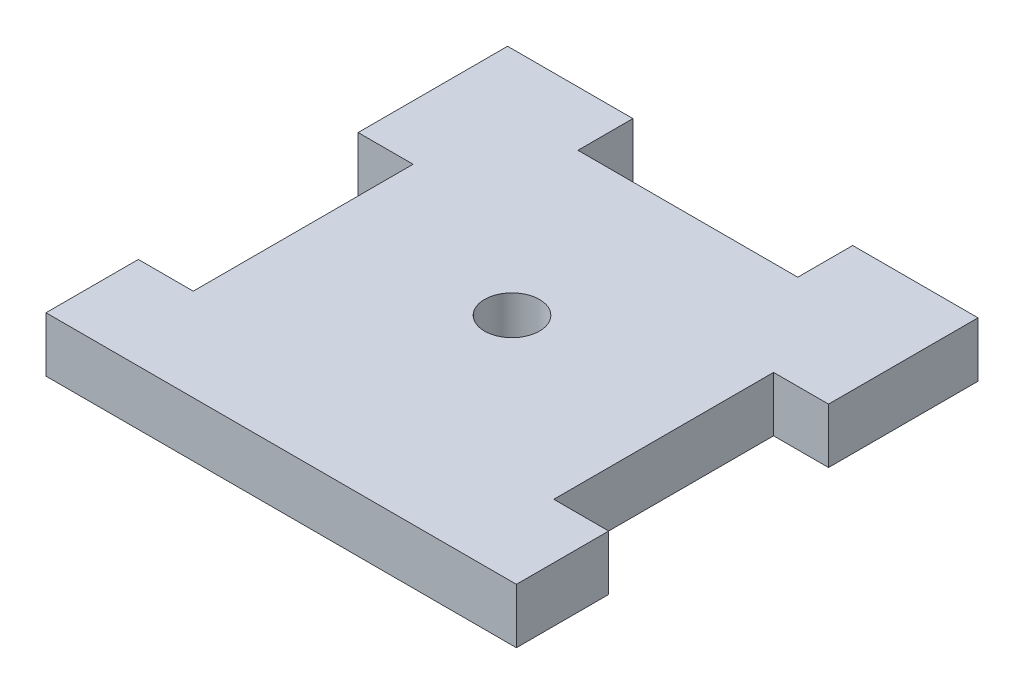
SolidWorks part; units mm, degrees
ref_plane "Front Plane" through (0, 0, 0) normal (0, 0, 1) x (1, 0, 0)
ref_plane "Top Plane" through (0, 0, 0) normal (0, 1, 0) x (1, 0, 0)
ref_plane "Right Plane" through (0, 0, 0) normal (1, 0, 0) x (0, 0, -1)
sketch "Sketch1" plane through (0, 0, 0) normal (0, 1, 0) x (1, 0, 0)
  line L0 (14.478, 53.34) -> (14.478, 46.99)
  line L1 (0, 0) -> (54.356, 0)
  line L2 (0, 0) -> (0, 10.668)
  line L3 (0, 53.34) -> (14.478, 53.34)
  line L4 (54.356, 0) -> (54.356, 10.668)
  line L5 (14.478, 46.99) -> (39.878, 46.99)
  line L6 (39.878, 46.99) -> (39.878, 53.34)
  line L7 (0, 36.068) -> (0, 53.34)
  line L8 (0, 36.068) -> (6.35, 36.068)
  line L9 (39.878, 53.34) -> (54.356, 53.34)
  line L10 (0, 10.668) -> (6.35, 10.668)
  line L11 (6.35, 36.068) -> (6.35, 10.668)
  line L12 (14.478, 53.34) -> (39.878, 53.34) construction
  line L13 (0, 36.068) -> (0, 10.668) construction
  line L14 (0, 0) -> (54.356, 53.34) construction
  line L15 (27.178, 26.67) -> (27.178, 53.34) construction
  line L16 (54.356, 10.668) -> (48.006, 10.668)
  line L17 (48.006, 36.068) -> (48.006, 10.668)
  line L18 (54.356, 36.068) -> (48.006, 36.068)
  line L19 (54.356, 36.068) -> (54.356, 53.34)
  circle A0 centre (27.178, 26.67) radius 3.175
  dimension "D8" = 6.35
  dimension "D1" = 6.35
  dimension "D2" = 6.35
  dimension "D3" = 25.4
  dimension "D4" = 25.4
  dimension "D5" = 53.34
  dimension "D6" = 17.272
  dimension "D7" = 54.356
extrude "Extrude1" add sketch "Sketch1" along normal blind 6.35
